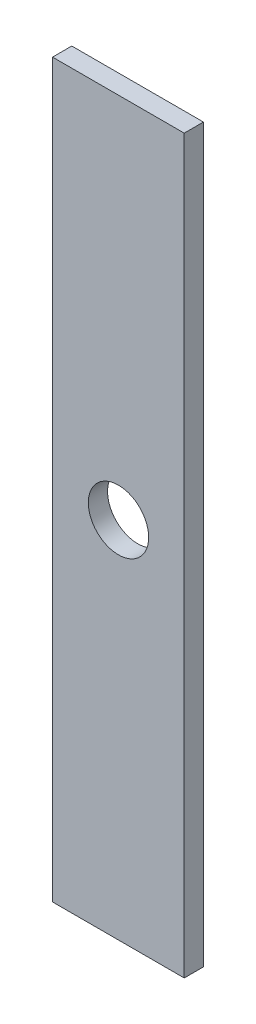
SolidWorks part; units mm, degrees
ref_plane "Front Plane" through (0, 0, 0) normal (0, 0, 1) x (1, 0, 0)
ref_plane "Top Plane" through (0, 0, 0) normal (0, 1, 0) x (1, 0, 0)
ref_plane "Right Plane" through (0, 0, 0) normal (1, 0, 0) x (0, 0, -1)
sketch "Sketch1" plane through (0, 0, 0) normal (0, 0, 1) x (1, 0, 0)
  line L1 (38.1, -211.709) -> (-38.1, -211.709)
  line L2 (38.1, -211.709) -> (38.1, 211.709)
  line L3 (38.1, 211.709) -> (-38.1, 211.709)
  line L4 (-38.1, -211.709) -> (-38.1, 211.709)
  line L5 (38.1, -211.709) -> (-38.1, 211.709) construction
  line L6 (38.1, 211.709) -> (-38.1, -211.709) construction
  point P0 (0, 0)
  dimension "D1" = 76.2
  dimension "D2" = 423.418
extrude "Boss-Extrude1" add sketch "Sketch1" along normal blind 11.1252
sketch "Sketch5" plane through (0, 0, 11.1252) normal (0, 0, 1) x (1, 0, 0)
  line L0 (-38.1, -211.709) -> (38.1, -211.709) construction
  line L2 (-38.1, 211.709) -> (-38.1, -211.709) construction
  circle A0 centre (0.0635, -1.2065) radius 17.4625
  dimension "D1" = 193.04
  dimension "D2" = 34.925
  dimension "D3" = 20.701
extrude "Cut-Extrude1" cut sketch "Sketch5" against normal through all
